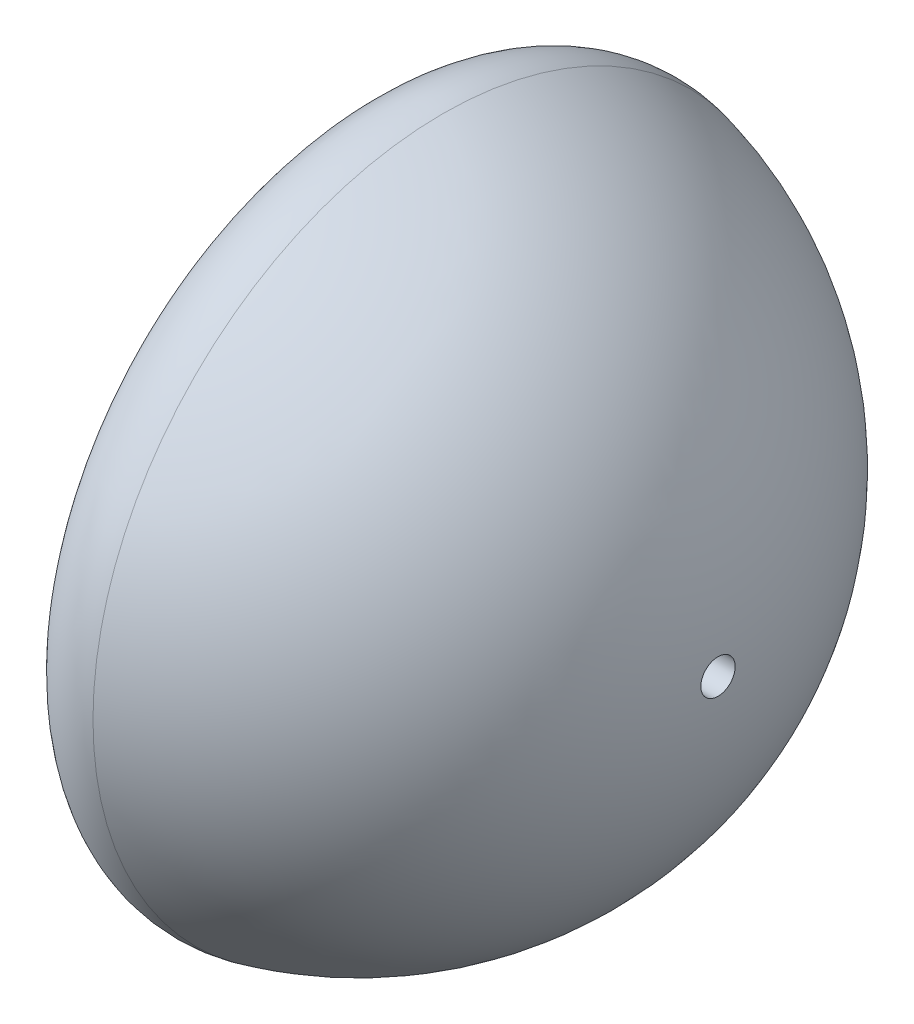
SolidWorks part; units mm, degrees
ref_plane "Front Plane" through (0, 0, 0) normal (0, 0, 1) x (1, 0, 0)
ref_plane "Top Plane" through (0, 0, 0) normal (0, 1, 0) x (1, 0, 0)
ref_plane "Right Plane" through (0, 0, 0) normal (1, 0, 0) x (0, 0, -1)
sketch "Sketch1" plane through (0, 0, 0) normal (0, 0, 1) x (1, 0, 0)
  line L0 (-111.3985, 2.4999) -> (-111.3985, -2.5002) construction
  line L3 (-111.3985, -0.0002) -> (-50111.3985, -0.0002) construction
  line L5 (-66.458, 2.4999) -> (-118.8985, 2.4999)
  line L6 (-103.8985, 2.4999) -> (-103.8985, 52.4999) construction
  line L7 (-103.8985, 52.4999) -> (-118.8985, 52.4999) construction
  line L8 (-118.8985, 2.4999) -> (-118.8985, 52.4999)
  arc A0 (-118.8985, 52.4999) -> (-66.458, 2.4999) centre (-118.8985, -0.0002) cw
  point P8 (-111.3985, -0.0002)
  dimension "D1" = 7.5
  dimension "D2" = 50
revolve "Revolve1" add sketch "Sketch1" angle 360 about L3
fillet "Fillet1" radius 10 1 edges at (-118.8985, 52.4999, 0)
